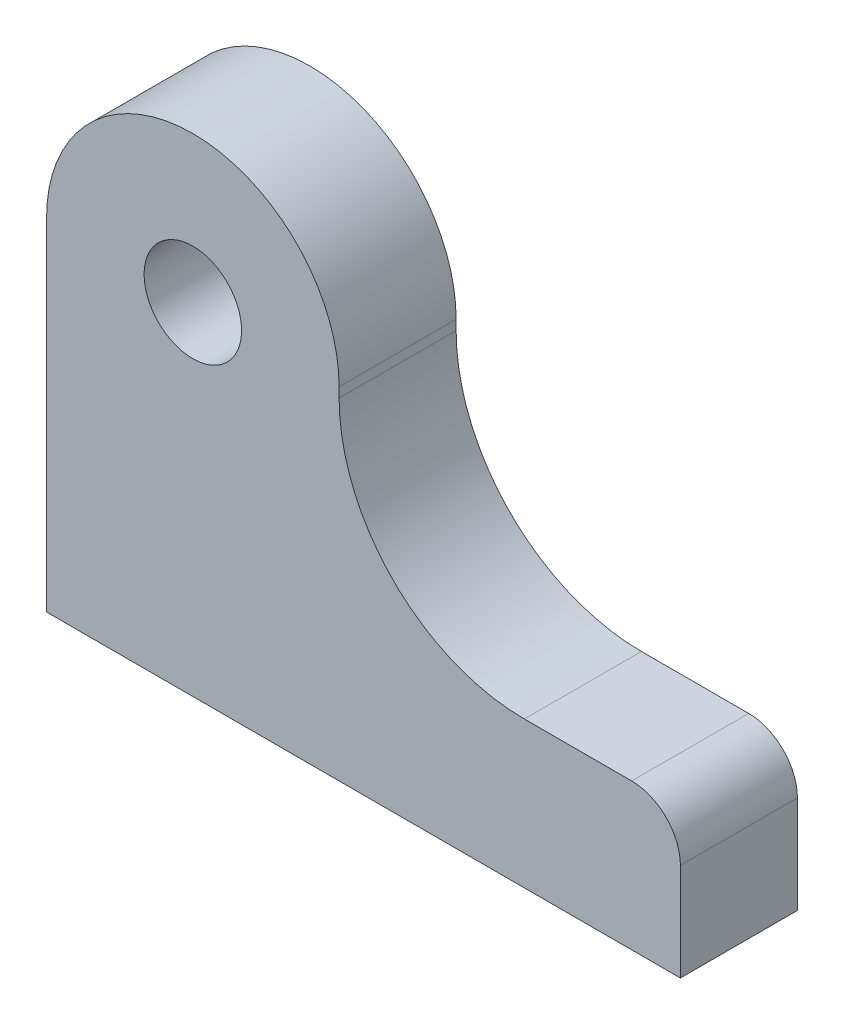
SolidWorks part; units mm, degrees
ref_plane "前视基准面" through (0, 0, 0) normal (0, 0, 1) x (1, 0, 0)
ref_plane "上视基准面" through (0, 0, 0) normal (0, 1, 0) x (1, 0, 0)
ref_plane "右视基准面" through (0, 0, 0) normal (1, 0, 0) x (0, 0, -1)
sketch "草图1" plane through (0, 0, 0) normal (0, 0, 1) x (1, 0, 0)
  line L1 (-32.5, -25) -> (32.5, -25)
  line L2 (-32.5, -25) -> (-32.5, 25)
  line L3 (-32.5, 25) -> (32.5, 25)
  line L4 (32.5, -25) -> (32.5, 25)
  line L5 (-32.5, -25) -> (32.5, 25) construction
  line L6 (-32.5, 25) -> (32.5, -25) construction
  point P0 (0, 0)
  dimension "D1" = 65
  dimension "D2" = 50
extrude "凸台-拉伸1" add sketch "草图1" along normal blind 12
sketch "草图2" plane through (0, -25, 0) normal (0, -1, 0) x (-1, 0, 0)
  line L1 (32.5, -12) -> (-32.5, -12) construction
  circle A1 centre (7.5, -6) radius 2.5
  circle A2 centre (-7.5, -6) radius 2.5
  circle A3 centre (-22.5, -6) radius 2.5
  dimension "D1" = 6
  dimension "D2" = 5
  dimension "D3" = 5
  dimension "D4" = 5
  dimension "D7" = 15
  dimension "D8" = 15
extrude "切除-拉伸1" cut sketch "草图2" against normal blind 10
sketch "草图3" plane through (0, 0, 0) normal (0, 0, -1) x (-1, 0, 0)
  line L0 (-32.5, 25) -> (32.5, 25) construction
  line L1 (32.5, 25) -> (32.5, -25) construction
  line L2 (-27.5, -10) -> (-16.5, -10)
  line L3 (-32.5, -25) -> (-32.5, 25) construction
  line L4 (2.5, 10) -> (2.5, 9)
  line L5 (32.5, -25) -> (-32.5, -25) construction
  line L12 (-32.5, -15) -> (-32.5, -10)
  line L14 (-32.5, -10) -> (-27.5, -10) construction
  line L15 (-32.5, -25) -> (-32.5, 25)
  line L16 (-32.5, 25) -> (32.5, 25)
  line L17 (32.5, 25) -> (32.5, -25)
  line L18 (-32.5, -10) -> (-32.5, 25)
  line L19 (-32.5, 25) -> (32.5, 25)
  line L20 (32.5, 25) -> (32.5, 10)
  arc A0 (32.5, 10) -> (2.5, 10) centre (17.5, 10) ccw
  arc A1 (-16.5, -10) -> (2.5, 9) centre (-16.5, 9) ccw
  arc A2 (-27.5, -10) -> (-32.5, -15) centre (-27.5, -15) ccw
  arc A3 (-32.5, -15) -> (-27.5, -10) centre (-27.5, -15) ccw construction
  line M2 (-32.5, 25) -> (-32.5, -25)
  line M4 (32.5, -25) -> (32.5, 25)
  line M5 (32.5, 25) -> (-32.5, 25)
  dimension "D1" = 30
  dimension "D2" = 19
  dimension "D5" = 10
  dimension "D3" = 15
  dimension "D4" = 0
extrude "切除-拉伸2" cut sketch "草图3" against normal blind 12 contours L2 A1 L4 A0 L19 M2 | A0 M4 M5
sketch "草图4" plane through (0, 0, 0) normal (0, 0, -1) x (-1, 0, 0)
  circle A0 centre (17.5, 10) radius 5
  dimension "D1" = 10
extrude "切除-拉伸3" cut sketch "草图4" against normal blind 12
sketch "草图5" plane through (-32.5, 0, 0) normal (-1, 0, 0) x (0, 0, 1)
  line L1 (12, -25) -> (0, -25) construction
  circle A1 centre (5, -15) radius 2.5
  dimension "D1" = 10
  dimension "D2" = 5
extrude "切除-拉伸4" cut sketch "草图5" against normal blind 10
